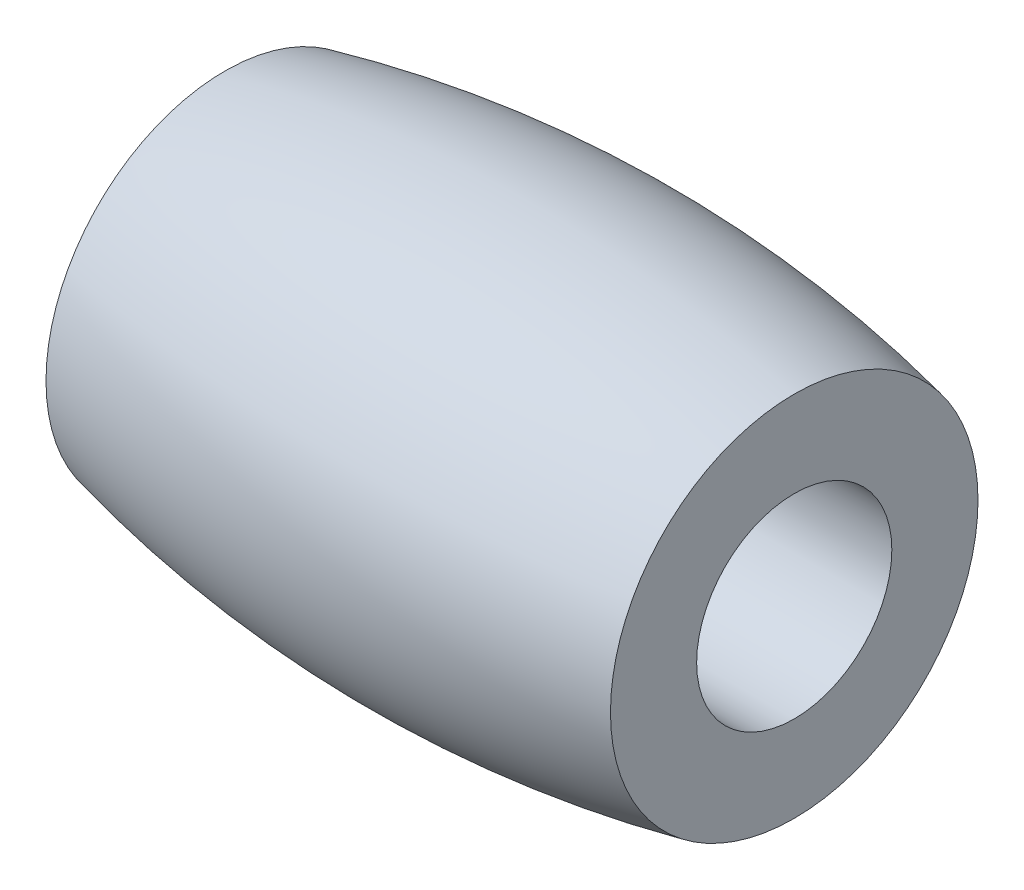
SolidWorks part; units mm, degrees
ref_plane "Front Plane" through (0, 0, 0) normal (0, 0, 1) x (1, 0, 0)
ref_plane "Top Plane" through (0, 0, 0) normal (0, 1, 0) x (1, 0, 0)
ref_plane "Right Plane" through (0, 0, 0) normal (1, 0, 0) x (0, 0, -1)
sketch "Sketch1" plane through (0, 0, 0) normal (0, 0, 1) x (1, 0, 0)
  line L0 (-13.2062, 0) -> (9.0188, 0)
  line L1 (-13.2062, 0) -> (-13.2062, 3.175)
  line L2 (9.0188, 0) -> (9.0188, 3.3638)
  line L3 (-13.2062, -3.81) -> (9.0188, -3.81) construction
  arc A0 (-13.2062, 3.175) -> (9.0188, 3.3638) centre (-1.6726, -46.2984) cw
  dimension "D2" = 3.81
  dimension "D1" = 22.225
revolve "Revolve1" add sketch "Sketch1" angle 360 about L3
